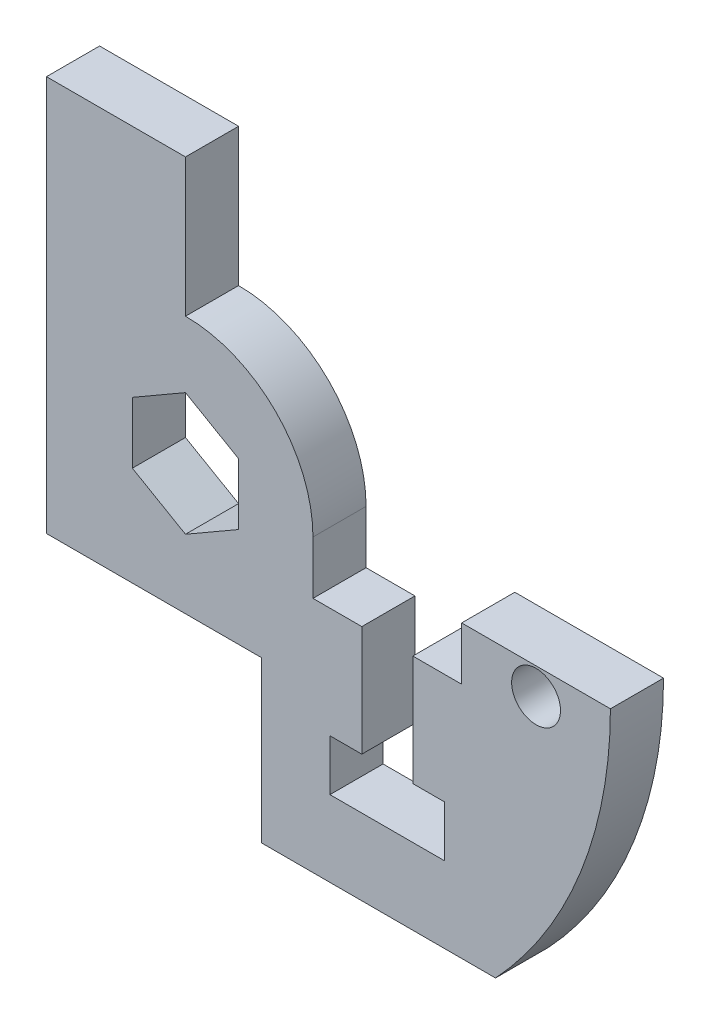
SolidWorks part; units mm, degrees
material "Acrylic (Medium-high impact)"
ref_plane "Front" through (0, 0, 0) normal (0, 0, 1) x (1, 0, 0)
ref_plane "Top" through (0, 0, 0) normal (0, 1, 0) x (1, 0, 0)
ref_plane "Right" through (0, 0, 0) normal (1, 0, 0) x (0, 0, -1)
sketch "Sketch1" plane through (0, 0, 0) normal (0, 0, 1) x (1, 0, 0)
  line L0 (0, 25.4) -> (0, 7.62)
  line L1 (3.175, -1.8331) -> (3.175, 1.8331)
  line L2 (3.175, 1.8331) -> (0, 3.6662)
  line L3 (0, 3.6662) -> (-3.175, 1.8331)
  line L4 (-3.175, 1.8331) -> (-3.175, -1.8331)
  line L5 (-3.175, -1.8331) -> (0, -3.6662)
  line L6 (0, -3.6662) -> (3.175, -1.8331)
  line L7 (25.4, 0) -> (7.62, 0)
  line L8 (16.51, 0) -> (25.4, 0)
  line L9 (7.62, 0) -> (16.51, 0)
  line L10 (7.62, 0) -> (7.62, -3.175)
  line L11 (7.62, -3.175) -> (16.51, -3.175)
  line L12 (16.51, 0) -> (16.51, -3.175)
  line L13 (10.541, -3.175) -> (13.589, -3.175)
  line L14 (10.541, -3.175) -> (10.541, -12.827)
  line L15 (10.541, -12.827) -> (13.589, -12.827)
  line L16 (13.589, -3.175) -> (13.589, -12.827)
  line L17 (8.636, -9.779) -> (15.494, -9.779)
  line L18 (8.636, -9.779) -> (8.636, -12.827)
  line L19 (8.636, -12.827) -> (15.494, -12.827)
  line L20 (15.494, -9.779) -> (15.494, -12.827)
  arc A0 (0, 25.4) -> (25.4, 0) centre (0, 0) ccw
  circle A1 centre (0, 0) radius 3.175 construction
  arc A2 (7.62, 0) -> (0, 7.62) centre (0, 0) ccw
  circle A3 centre (20.955, -1.5875) radius 1.4605
  point P20 (12.065, -3.175)
  point P21 (12.065, -12.827)
  point P24 (12.065, -12.827)
  point P30 (16.51, -1.5875)
  point P32 (20.955, 0)
  dimension "D1" = 50.8
  dimension "D2" = 6.35
  dimension "D8" = 2.921
  dimension "D3" = 17.78
  dimension "D4" = 8.89
  dimension "D5" = 3.175
  dimension "D6" = 3.048
  dimension "D7" = 9.652
  dimension "D9" = 3.048
  dimension "D10" = 6.858
extrude "Boss-Extrude1" add sketch "Sketch1" along normal blind 3.175 contours L10 A2 L0 A0 L7 L12 L11 L16 L17 L20 L19 L15 L18 L14 A3 L6 L5 L4 L3 L2 L1
sketch "Sketch2" plane through (0, 0, -93.472) normal (0, 0, -1) x (-1, 0, 0)
  line L2 (-4.5387, -7.7825) -> (27.8344, -7.7825)
  line L3 (27.8344, -7.7825) -> (16.0893, -38.126)
  line L5 (-4.5387, -7.7825) -> (-4.5387, -36.4274)
  line L6 (-4.5387, -36.4274) -> (16.0893, -38.126)
extrude "Cut-Extrude1" cut sketch "Sketch2" against normal up to next
sketch "Sketch3" plane through (0, 0, -93.472) normal (0, 0, -1) x (-1, 0, 0)
  line L0 (8.3087, -7.7825) -> (8.3087, 15.867)
  line L1 (24.1784, -7.7825) -> (-4.5387, -7.7825) construction
  line L2 (8.3087, 15.867) -> (0, 15.867)
  line L3 (0, 25.4) -> (0, 7.62) construction
  line L4 (0, 15.867) -> (0, 32.2123)
  line L5 (0, 32.2123) -> (53.9066, 11.4206)
  line L6 (53.9066, 11.4206) -> (19.5878, -19.2642)
  line L7 (2.4522, -20.1413) -> (45.5757, -17.934) construction
  line L8 (19.5878, -19.2642) -> (8.3087, -7.7825)
extrude "Cut-Extrude2" cut sketch "Sketch3" against normal up to next
sketch "Sketch4" plane through (0, 0, 0) normal (0, 0, -1) x (-1, 0, 0)
  line L1 (-4.5387, -24.9912) -> (-29.9387, -24.9912)
  line L2 (-4.5387, -24.9912) -> (-4.5387, -17.3712)
  line L3 (-4.5387, -17.3712) -> (-29.9387, -17.3712)
  line L4 (-29.9387, -24.9912) -> (-29.9387, -17.3712)
  dimension "D1" = 7.62
  dimension "D2" = 25.4
extrude "Cut-Extrude3" cut sketch "Sketch4" against normal through all
